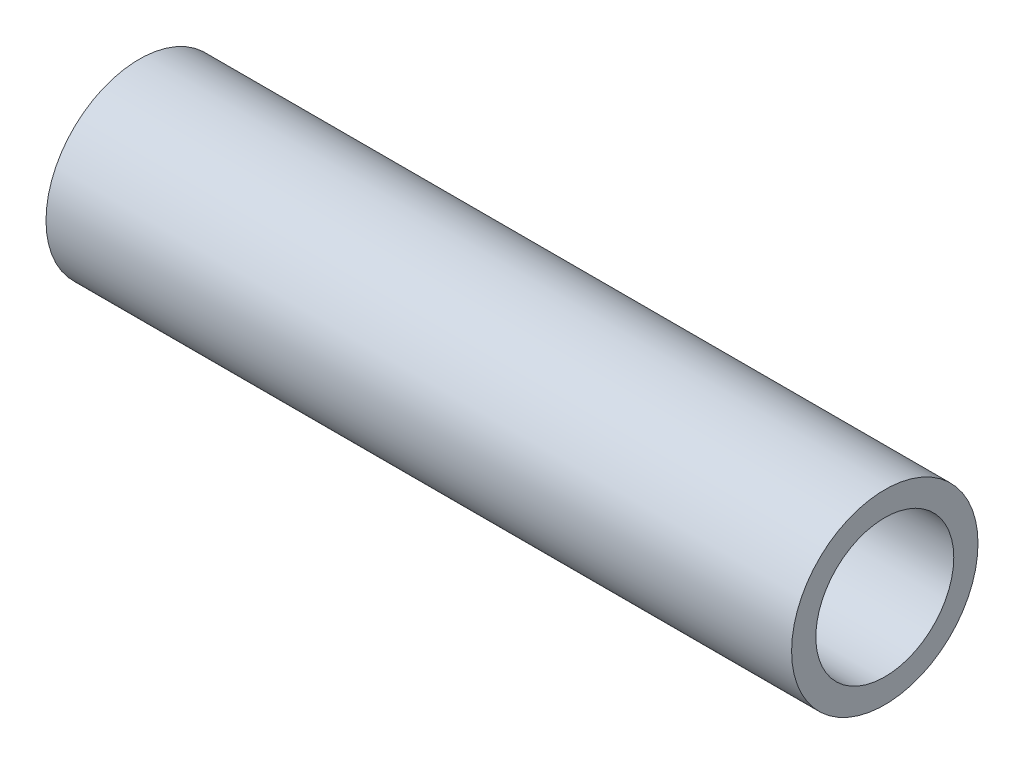
SolidWorks part; units mm, degrees
material "6061-T6 (SS)"
ref_plane "Front Plane" through (0, 0, 0) normal (0, 0, 1) x (1, 0, 0)
ref_plane "Top Plane" through (0, 0, 0) normal (0, 1, 0) x (1, 0, 0)
ref_plane "Right Plane" through (0, 0, 0) normal (1, 0, 0) x (0, 0, -1)
sketch "Sketch1" plane through (0, 0, 0) normal (1, 0, 0) x (0, 0, -1)
  circle A0 centre (0, 0) radius 4.699
  circle A1 centre (0, 0) radius 6.35
  dimension "D1" = 1.651
  dimension "D2" = 12.7
extrude "Boss-Extrude1" add sketch "Sketch1" along normal mid plane 50.8
